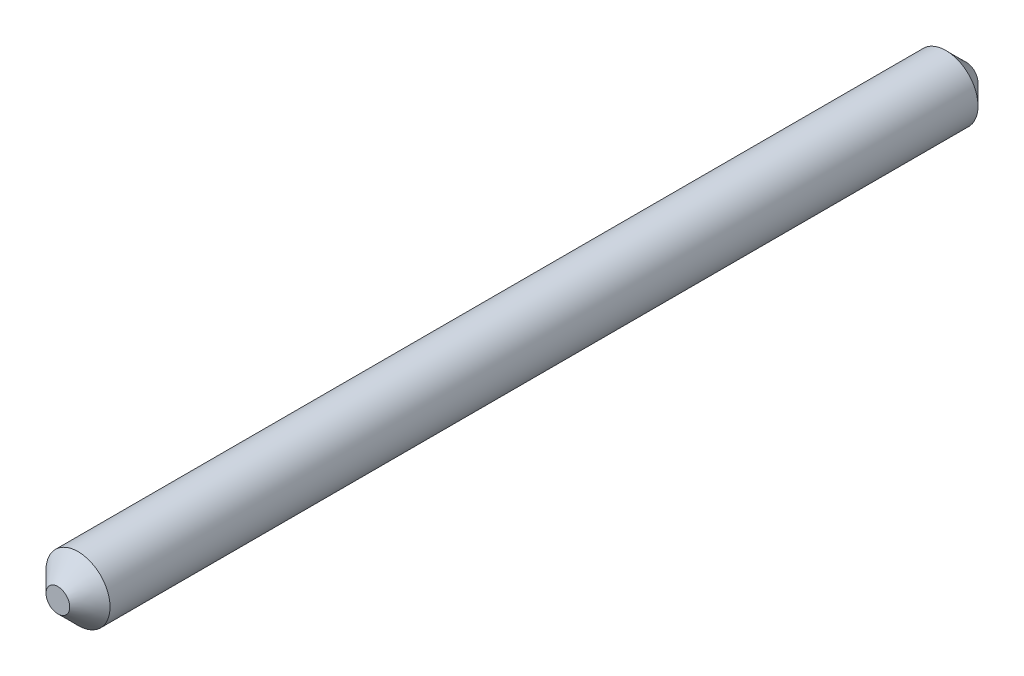
SolidWorks part; units mm, degrees
material "Plain Carbon Steel"
ref_plane "Front Plane" through (0, 0, 0) normal (0, 0, 1) x (1, 0, 0)
ref_plane "Top Plane" through (0, 0, 0) normal (0, 1, 0) x (1, 0, 0)
ref_plane "Right Plane" through (0, 0, 0) normal (1, 0, 0) x (0, 0, -1)
sketch "Sketch2" plane through (0, 0, 0) normal (0, 0, 1) x (1, 0, 0)
  circle A0 centre (0, 0) radius 1.5875
  dimension "D1" = 3.175
extrude "Boss-Extrude1" add sketch "Sketch2" along normal mid plane 45
chamfer "Chamfer1" distance 1 angle 45 2 edges at (1.5875, 0, 22.5) (1.5875, 0, -22.5)
